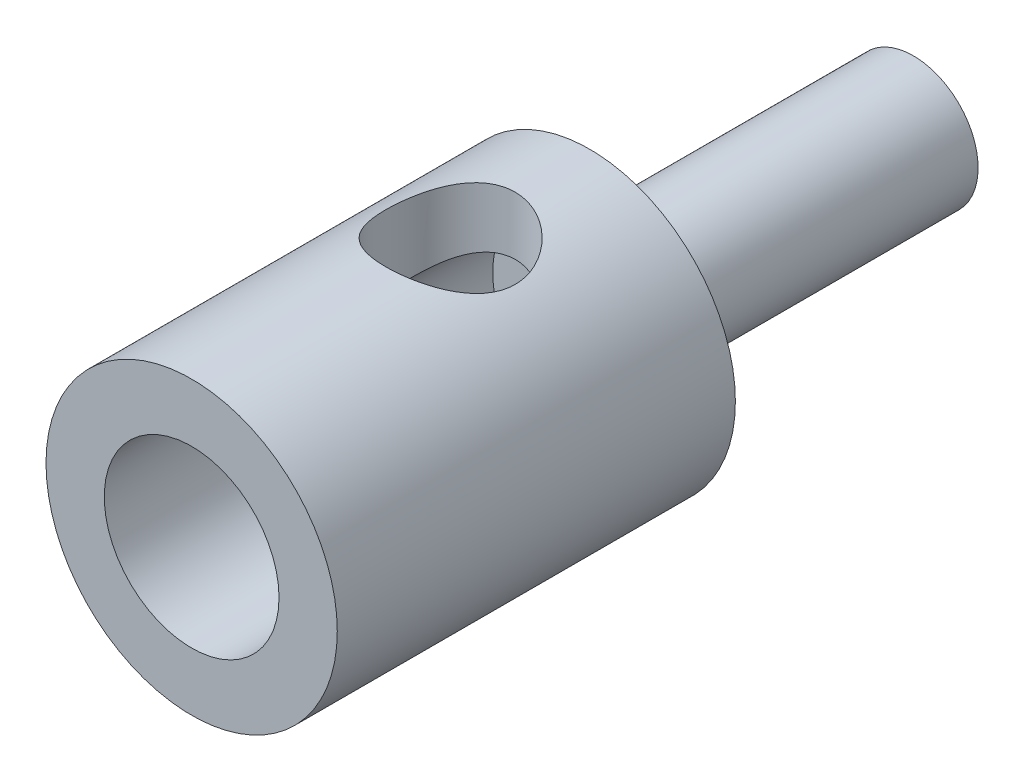
SolidWorks part; units mm, degrees
material "AISI 304"
ref_plane "Front Plane" through (0, 0, 0) normal (0, 0, 1) x (1, 0, 0)
ref_plane "Top Plane" through (0, 0, 0) normal (0, 1, 0) x (1, 0, 0)
ref_plane "Right Plane" through (0, 0, 0) normal (1, 0, 0) x (0, 0, -1)
sketch "Sketch1" plane through (0, 0, 0) normal (0, 0, 1) x (1, 0, 0)
  circle A0 centre (0, 0) radius 2.25
  dimension "D1" = 4.5
extrude "Boss-Extrude1" add sketch "Sketch1" along normal blind 6.15
sketch "Sketch2" plane through (0, 0, 0) normal (0, 0, -1) x (-1, 0, 0)
  circle A0 centre (0, 0) radius 1
  dimension "D1" = 2
extrude "Boss-Extrude2" add sketch "Sketch2" along normal blind 5
sketch "Sketch3" plane through (0, 0, 6.15) normal (0, 0, 1) x (1, 0, 0)
  circle A0 centre (0, 0) radius 1.35
  dimension "D1" = 2.7
extrude "Cut-Extrude1" cut sketch "Sketch3" against normal blind 6
ref_plane "Linkage-Hole-Plane" through (0, -2.25, 0) normal (0, -1, 0) x (-1, 0, 0)
sketch "Sketch4" plane through (0, -2.25, 0) normal (0, -1, 0) x (-1, 0, 0)
  line L0 (1, 0) -> (-1, 0) construction
  circle A0 centre (0, -2.15) radius 1
  dimension "D2" = 2
  dimension "D1" = 2.15
extrude "Cut-Extrude2" cut sketch "Sketch4" against normal blind 6
